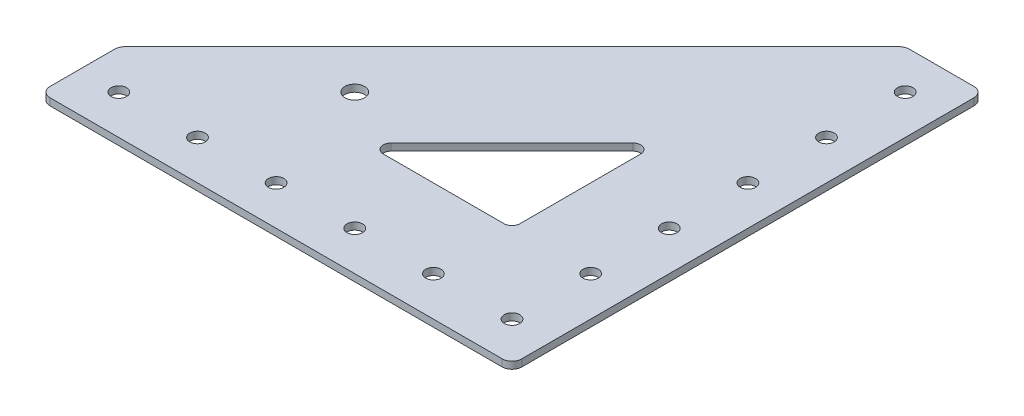
SolidWorks part; units mm, degrees
material "6061-T6 (SS)"
ref_plane "Front Plane" through (0, 0, 0) normal (0, 0, 1) x (1, 0, 0)
ref_plane "Top Plane" through (0, 0, 0) normal (0, 1, 0) x (1, 0, 0)
ref_plane "Right Plane" through (0, 0, 0) normal (1, 0, 0) x (0, 0, -1)
sketch "Sketch1" plane through (0, 0, 0) normal (0, 1, 0) x (1, 0, 0)
  line L0 (0, 0) -> (0, 152.4)
  line L1 (0, 152.4) -> (-25.4, 152.4)
  line L2 (-25.4, 152.4) -> (-152.4, 25.4)
  line L3 (-152.4, 25.4) -> (-152.4, 0)
  line L4 (-152.4, 0) -> (0, 0)
  circle A0 centre (-12.7, 12.7) radius 2.4892
  circle A1 centre (-38.1, 12.7) radius 2.4892
  circle A2 centre (-63.5, 12.7) radius 2.4892
  circle A3 centre (-88.9, 12.7) radius 2.4892
  circle A4 centre (-114.3, 12.7) radius 2.4892
  circle A5 centre (-12.7, 38.1) radius 2.4892
  circle A6 centre (-12.7, 63.5) radius 2.4892
  circle A7 centre (-12.7, 88.9) radius 2.4892
  circle A8 centre (-12.7, 114.3) radius 2.4892
  circle A9 centre (-139.7, 12.7) radius 2.4892
  circle A13 centre (-12.7, 139.7) radius 2.4892
  circle A17 centre (-101.6, 50.8) radius 3.175
  dimension "D4" = 12.7
  dimension "D5" = 12.7
  dimension "D11" = 6.35
  dimension "D12" = 4.9784
  dimension "D1" = 152.4
  dimension "D2" = 25.4
  dimension "D3" = 152.4
  dimension "D8" = 101.6
  dimension "D9" = 50.8
  dimension "D10" = 25.4
  dimension "D6" = 6
  dimension "D7" = 6
extrude "Boss-Extrude2" add sketch "Sketch1" along normal mid plane 2.286
fillet "Fillet1" radius 3.175 2 edges at (0, 0, 0) (-152.4, 0, 0)
fillet "Fillet2" radius 3.175 3 edges at (-152.4, 0, -25.4) (-25.4, 0, -152.4) (0, 0, -152.4)
sketch "Sketch2" plane through (0, 1.143, 0) normal (0, 1, 0) x (1, 0, 0)
  line L1 (0, 0) -> (-152.4, 0)
  line L2 (0, 0) -> (0, 152.4)
  line L3 (0, 152.4) -> (-152.4, 152.4)
  line L4 (-152.4, 0) -> (-152.4, 152.4)
  line L20 (-38.1, 85.8185) -> (-85.8185, 38.1)
  line L21 (-85.8185, 38.1) -> (-38.1, 38.1)
  line L22 (-38.1, 38.1) -> (-38.1, 85.8185)
  line L23 (-38.1, 85.8185) -> (-85.8185, 38.1)
  line L24 (-85.8185, 38.1) -> (-38.1, 38.1)
  line L25 (-38.1, 38.1) -> (-38.1, 85.8185)
  dimension "D1" = 152.4
  dimension "D2" = 152.4
  dimension "D3" = 152.4
  dimension "D4" = 38.1
extrude "Cut-Extrude1" cut sketch "Sketch2" against normal blind 2.54 flip side to cut
fillet "Fillet3" radius 2.54 3 edges at (-38.1, 0, -38.1) (-85.8185, 0, -38.1) (-38.1, 0, -85.8185)
